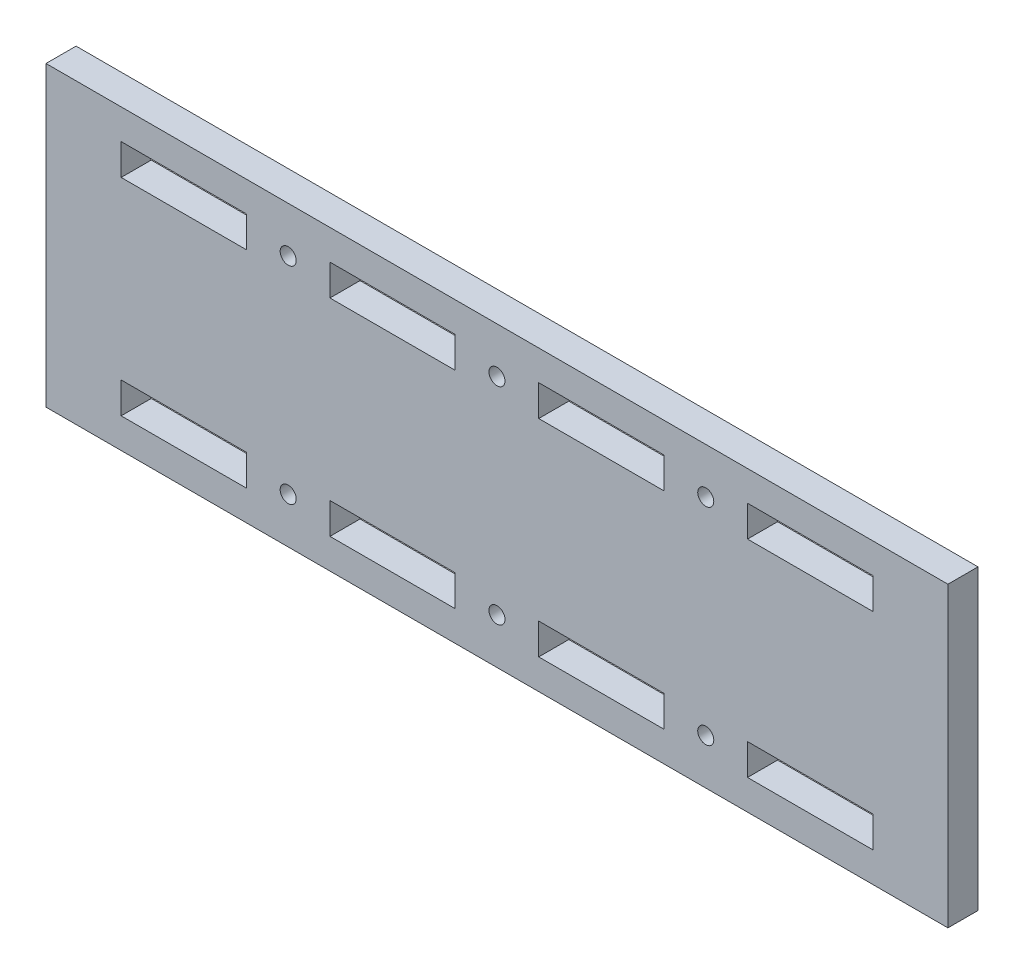
SolidWorks part; units mm, degrees
material "Oak"
ref_plane "Front Plane" through (0, 0, 0) normal (0, 0, 1) x (1, 0, 0)
ref_plane "Top Plane" through (0, 0, 0) normal (0, 1, 0) x (1, 0, 0)
ref_plane "Right Plane" through (0, 0, 0) normal (1, 0, 0) x (0, 0, -1)
sketch "Sketch1" plane through (0, 0, 0) normal (0, 0, 1) x (1, 0, 0)
  line L0 (-33.3333, -17.5) -> (-33.3333, -23.7)
  line L1 (-90, -29.7) -> (90, -29.7)
  line L2 (-90, -29.7) -> (-90, 29.7)
  line L3 (-90, 29.7) -> (90, 29.7)
  line L4 (90, -29.7) -> (90, 29.7)
  line L5 (-90, -29.7) -> (90, 29.7) construction
  line L6 (-90, 29.7) -> (90, -29.7) construction
  line L7 (-75, -17.5) -> (-50, -17.5)
  line L8 (-75, -17.5) -> (-75, -23.7)
  line L9 (-75, -23.7) -> (-50, -23.7)
  line L10 (-50, -17.5) -> (-50, -23.7)
  line L11 (-33.3333, -17.5) -> (-8.3333, -17.5)
  line L12 (-8.3333, -17.5) -> (-8.3333, -23.7)
  line L13 (-33.3333, -23.7) -> (-8.3333, -23.7)
  line L14 (8.3333, -17.5) -> (8.3333, -23.7)
  line L15 (8.3333, -17.5) -> (33.3333, -17.5)
  line L16 (33.3333, -17.5) -> (33.3333, -23.7)
  line L17 (8.3333, -23.7) -> (33.3333, -23.7)
  line L18 (50, -17.5) -> (50, -23.7)
  line L19 (50, -17.5) -> (75, -17.5)
  line L20 (75, -17.5) -> (75, -23.7)
  line L21 (50, -23.7) -> (75, -23.7)
  line L22 (-50, -20.6) -> (-33.3333, -20.6) construction
  line L23 (-8.3333, -20.6) -> (8.3333, -20.6) construction
  line L24 (-75, 23.7) -> (-75, 17.5)
  line L25 (-75, 23.7) -> (-50, 23.7)
  line L26 (-50, 23.7) -> (-50, 17.5)
  line L27 (-75, 17.5) -> (-50, 17.5)
  line L28 (-33.3333, 23.7) -> (-33.3333, 17.5)
  line L29 (-33.3333, 17.5) -> (-8.3333, 17.5)
  line L30 (-8.3333, 23.7) -> (-8.3333, 17.5)
  line L31 (-33.3333, 23.7) -> (-8.3333, 23.7)
  line L32 (8.3333, 23.7) -> (8.3333, 17.5)
  line L33 (8.3333, 17.5) -> (33.3333, 17.5)
  line L34 (33.3333, 23.7) -> (33.3333, 17.5)
  line L35 (8.3333, 23.7) -> (33.3333, 23.7)
  line L36 (50, 23.7) -> (50, 17.5)
  line L37 (50, 17.5) -> (75, 17.5)
  line L38 (75, 23.7) -> (75, 17.5)
  line L39 (50, 23.7) -> (75, 23.7)
  circle A10 centre (-41.6667, -20.6) radius 1.6
  circle A11 centre (0, -20.6) radius 1.6
  circle A12 centre (41.6667, -20.6) radius 1.6
  circle A13 centre (0, 20.6) radius 1.6
  circle A14 centre (41.6667, 20.6) radius 1.6
  circle A15 centre (-41.6667, 20.6) radius 1.6
  point P0 (0, 0)
  point P28 (-50, 20.6)
  dimension "D9" = 3.2
  dimension "D1" = 180
  dimension "D2" = 15
  dimension "D3" = 25
  dimension "D4" = 6
  dimension "D5" = 6.2
  dimension "D6" = 6
  dimension "D7" = 4
  dimension "D8" = 15
  dimension "D12" = 35
  dimension "D11" = 2
  dimension "D10" = 3
  dimension "D13" = 2
extrude "Boss-Extrude1" add sketch "Sketch1" along normal blind 6
